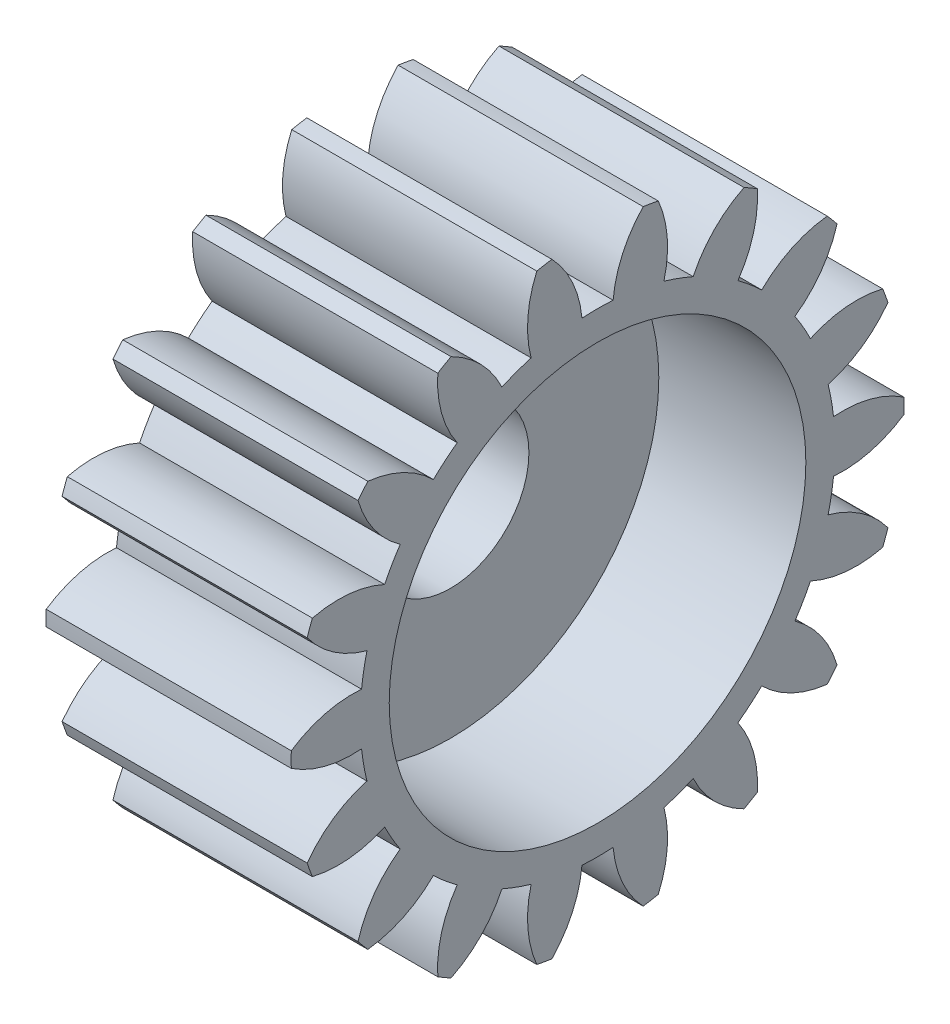
SolidWorks part; units mm, degrees
ref_plane "Plane1" through (0, 0, 0) normal (0, 0, 1) x (1, 0, 0)
ref_plane "Plane2" through (0, 0, 0) normal (0, 1, 0) x (1, 0, 0)
ref_plane "Plane3" through (0, 0, 0) normal (1, 0, 0) x (0, 0, -1)
sketch "HoldingSke" plane through (0, 0, 0) normal (0, 1, 0) x (1, 0, 0)
  line L0 (0, 0) -> (0.7608, -0.2472)
  line L1 (-15, 0) -> (100, 0) construction
  line L2 (0, 0) -> (-2.1039, 2.3779)
  line L3 (0, 0) -> (-11.863, 4.5341)
  line L4 (0, 0) -> (8.2133, 2.6687)
  line L5 (0, 0) -> (-46.8476, -17.4728)
  line L6 (0, 0) -> (-8.2896, -5.593)
  line L7 (-2.1039, 2.3779) -> (8.6586, 51.2059)
  line L8 (-76.2, 54.61) -> (-75.7, 54.61)
  line L9 (-71.009, 38.7566) -> (-53.1078, 45.2721)
  line L10 (-76.2, 71.12) -> (104.1128, 71.12)
  line L11 (0, 0) -> (-10, 0)
  line L12 (-76.2, 101.6) -> (-76.155, 101.6)
  line L13 (24.9733, 27.94) -> (52.9518, 28.4284)
  line L14 (24.9733, 27.94) -> (24.9743, 27.94)
  line L15 (24.9733, 27.94) -> (100.4006, 29.5858)
  line L16 (-63.627, -1.25) -> (-12.827, -1.25)
  circle A0 centre (0, 0) radius 1.5
  circle A1 centre (0, 0) radius 9.6865
  circle A2 centre (0, 0) radius 37.5
  circle A3 centre (0, 0) radius 1.5
  dimension "MHD" = 19.373
  dimension "Hub_dia" = 75
  dimension "Bore" = 3
  dimension "MBD" = 3
  dimension "Num_teeth" = 18
  dimension "Pitch" = 0.8
  dimension "Overall_len" = 50
  dimension "Show_teeth" = 18
  dimension "Thickness" = 10
  dimension "OAL" = 50.0001
  dimension "T_dim" = 0.5
  dimension "Ap" = 20
  dimension "H" = 19.05
  dimension "Pitch_radius" = 180.3128
  dimension "Width" = 10
  dimension "Backlash" = 0.045
  dimension "Addendum_fac" = 1
  dimension "Dedendum_fac" = 1.25
  dimension "Clearance_fac" = 0.25
  dimension "Dedendum_add" = 0.001
  dimension "Module" = 1.25
sketch "BasProSke" plane through (0, 0, 0) normal (0, 1, 0) x (1, 0, 0)
  line L0 (-10, 0) -> (60, 0) construction
  line L1 (0, 0) -> (0, 12.5)
  line L2 (0, 0) -> (10, 0)
  line L3 (10, 0) -> (10, 12.5)
  line L4 (10, 12.5) -> (0, 12.5)
  dimension "Thickness" = 10
  dimension "Diameter" = 25
revolve "Base-Revolve" add sketch "BasProSke" angle 360 about L0
sketch "TooCutSke" plane through (0, 0, 0) normal (1, 0, 0) x (0, 0, -1)
  line L1 (0, 0) -> (0, 107) construction
  line L2 (0, 0) -> (-1.0592, 11.2) construction
  line L3 (0, 0) -> (-3.8945, 22.0869) construction
  line L4 (-1.0592, 11.2) -> (-1.9473, 11.0434) construction
  arc A0 (0.6346, 9.6657) -> (-0.6346, 9.6657) centre (0, 0) ccw
  arc A1 (1.8837, 12.3829) -> (-1.8837, 12.3829) centre (0, 0) ccw
  circle A2 centre (0, 0) radius 11.25 construction
  circle A3 centre (0, 0) radius 10.5715 construction
  arc A4 (-0.6346, 9.6657) -> (-1.8837, 12.3829) centre (-5.1154, 9.2515) ccw
  arc A5 (1.8837, 12.3829) -> (0.6346, 9.6657) centre (5.1154, 9.2515) ccw
  dimension "Root_dia" = 19.373
  dimension "Overcut_dia" = 25.0508
  dimension "Pitch_dia" = 22.5
  dimension "Base_dia" = 21.1431
  dimension "Flank_rad" = 4.5
  dimension "Half_ang" = 10
  dimension "Half_CT" = 0.9018
extrude "ToothCut" cut sketch "TooCutSke" along normal through all
fillet "Breaks" [suppressed] radius 0.025
fillet "RootFillets" [suppressed] radius 0.3135
pattern_circular "TeethCuts" count 18 every 20 about axis through (-10, 0, 0) along (1, 0, 0) of "ToothCut", "RootFillets", "Breaks"
sketch "HubNeaOneSke" plane through (0, 0, 0) normal (-1, 0, 0) x (0, 0, 1)
  circle A0 centre (0, 0) radius 9.6865
  dimension "Diameter" = 19.373
extrude "HubNearOne" [suppressed] add sketch "HubNeaOneSke" along normal blind 40.0001
sketch "HubNeaBotSke" plane through (0, 0, 0) normal (-1, 0, 0) x (0, 0, 1)
  circle A0 centre (0, 0) radius 9.6865
  dimension "Diameter" = 19.373
extrude "HubNearBoth" [suppressed] add sketch "HubNeaBotSke" along normal blind 20
ref_plane "FarPln" through (10, 0, 0) normal (1, 0, 0) x (0, 0, -1)
sketch "HubFarSke" plane through (10, 0, 0) normal (1, 0, 0) x (0, 0, -1)
  circle A0 centre (0, 0) radius 9.6865
  dimension "Diameter" = 19.373
extrude "HubFar" [suppressed] add sketch "HubFarSke" along normal blind 20
sketch "BorSke" plane through (0, 0, 0) normal (1, 0, 0) x (0, 0, -1)
  circle A0 centre (0, 0) radius 1.5
  dimension "Diameter" = 3
extrude "Bore" cut sketch "BorSke" along normal mid plane 100.0001
sketch "KeySke" plane through (0, 0, 0) normal (1, 0, 0) x (0, 0, -1)
  line L0 (-0.6, 0) -> (-0.6, 2)
  line L1 (-0.6, 2) -> (0.6, 2)
  line L2 (0.6, 2) -> (0.6, 0)
  line L3 (0, 0) -> (0, 34) construction
  line L4 (-0.6, 0) -> (0.6, 0)
  dimension "Offset" = 2
  dimension "Width" = 1.2
extrude "Keyway" [suppressed] cut sketch "KeySke" along normal mid plane 100.0001
pattern_circular "Keyway2" [suppressed] count 2 every 90 about axis through (-10, 0, 0) along (1, 0, 0)
sketch "Sketch1" plane through (10, 0, 0) normal (1, 0, 0) x (0, 0, -1)
  circle A0 centre (0, 0) radius 8.5
  dimension "D1" = 17
extrude "Cut-Extrude1" cut sketch "Sketch1" against normal blind 6
sketch "Sketch2" plane through (4, 0, 0) normal (1, 0, 0) x (0, 0, -1)
  circle A0 centre (0, 0) radius 3.2
  dimension "D1" = 6.4
extrude "Cut-Extrude2" cut sketch "Sketch2" against normal through all
equation "' \"Module@HoldingSke\" = 6.35"
equation "' \"Num_teeth@HoldingSke\" = 12"
equation "' \"Ap@HoldingSke\" =  20"
equation "' \"Ap@HoldingSke\" = 20"
equation "' \"Width@HoldingSke\" = 0.5 * 25.4"
equation "' \"Hub_dia@HoldingSke\"= 1 * 25.4"
equation "' \"Hub_dia@HoldingSke\" = 1 * 25.4"
equation "' \"Overall_len@HoldingSke\" = 1.0 * 25.4"
equation "' \"Bore@HoldingSke\" = 0.75 * 25.4"
equation "' \"T_dim@HoldingSke\" = 0.1 * 25.4"
equation "' \"Width@KeySke\" = 0.25 * 25.4"
equation "' \"Show_teeth@HoldingSke\" = 13"
equation "' \"Backlash@HoldingSke\" = 0.009 * 25.4"
equation "' \"Addendum_fac@HoldingSke\" = 1.0"
equation "' \"Dedendum_fac@HoldingSke\" = 1.25"
equation "' \"Dedendum_add@HoldingSke\" = 0.00005 * 25.4"
equation "' \"Clearance_fac@HoldingSke\" = 0.25"
equation "\"Pitch@HoldingSke\" = 1 / \"Module@HoldingSke\""
equation "\"Overcut_dia@TooCutSke\" = (\"Num_teeth@HoldingSke\" + 2 * \"Addendum_fac@HoldingSke\") / \"Pitch@HoldingSke\" + 0.002 * 25.4"
equation "\"Pitch_dia@TooCutSke\" = \"Num_teeth@HoldingSke\" / \"Pitch@HoldingSke\""
equation "\"Base_dia@TooCutSke\" = \"Num_teeth@HoldingSke\" / \"Pitch@HoldingSke\" * cos((\"Ap@HoldingSke\"  * 3.14159265 / 180))"
equation "\"Root_dia@TooCutSke\" = (\"Num_teeth@HoldingSke\" + 2) / \"Pitch@HoldingSke\" - 2 * (\"Addendum_fac@HoldingSke\" + \"Dedendum_fac@HoldingSke\") / \"Pitch@HoldingSke\" - \"Dedendum_add@HoldingSke\" * 2"
equation "\"Half_ang@TooCutSke\" = 180 / \"Num_teeth@HoldingSke\""
equation "\"Half_CT@TooCutSke\" = \"Num_teeth@HoldingSke\" / \"Pitch@HoldingSke\" * sin((3.14159265 / 2 / \"Num_teeth@HoldingSke\")) / 2 - 7 * \"Backlash@HoldingSke\" / 4"
equation "\"Flank_rad@TooCutSke\" = \"Num_teeth@HoldingSke\" / \"Pitch@HoldingSke\" / 5"
equation "\"Radius@RootFillets\" = \"Clearance_fac@HoldingSke\" / \"Pitch@HoldingSke\" + \"Dedendum_add@HoldingSke\""
equation "\"Break_rad@Breaks\" = 0.02 / \"Pitch@HoldingSke\""
equation "\"Thickness@HoldingSke\" = \"Width@HoldingSke\""
equation "\"OAL@HoldingSke\" = \"Thickness@HoldingSke\""
equation "\"MHD@HoldingSke\" = (\"Num_teeth@HoldingSke\" + 2) / \"Pitch@HoldingSke\" - 2 * (\"Addendum_fac@HoldingSke\" + \"Dedendum_fac@HoldingSke\")  / \"Pitch@HoldingSke\" - \"Dedendum_add@HoldingSke\" * 2"
equation "\"MBD@HoldingSke\" = (\"Num_teeth@HoldingSke\" + 2) / \"Pitch@HoldingSke\" - 2 * (\"Addendum_fac@HoldingSke\" + \"Dedendum_fac@HoldingSke\")  / \"Pitch@HoldingSke\" - \"Dedendum_add@HoldingSke\" * 2 - 0.002 * 25.4"
equation "\"MHD@HoldingSke\" = ((sgn( \"MHD@HoldingSke\" - \"Hub_dia@HoldingSke\" )-1)*( \"MHD@HoldingSke\" - \"Hub_dia@HoldingSke\" ))/-2+ \"Hub_dia@HoldingSke\""
equation "\"MBD@HoldingSke\" = ((sgn( \"MBD@HoldingSke\" - \"Bore@HoldingSke\" )-1)*( \"MBD@HoldingSke\" - \"Bore@HoldingSke\" ))/-2+ \"Bore@HoldingSke\""
equation "\"OAL@HoldingSke\" = ((sgn( \"OAL@HoldingSke\" - \"Overall_len@HoldingSke\" )+1)*( \"OAL@HoldingSke\" - \"Overall_len@HoldingSke\" ))/2 + \"Overall_len@HoldingSke\" + 0.000002 * 25.4"
equation "\"Num_teeth@TeethCuts\" = int( \"Show_teeth@HoldingSke\" ) + 1"
equation "\"Num_teeth@TeethCuts\" = ((sgn( \"Num_teeth@TeethCuts\" - \"Num_teeth@HoldingSke\" )-1)*( \"Num_teeth@TeethCuts\" - \"Num_teeth@HoldingSke\" ))/-2+ \"Num_teeth@HoldingSke\""
equation "\"Num_teeth@TeethCuts\" = ((sgn( \"Num_teeth@TeethCuts\" - 2.0)+1)*( \"Num_teeth@TeethCuts\" - 2.0))/2 +2.0"
equation "\"Angle@TeethCuts\" = 360.0 / \"Num_teeth@HoldingSke\""
equation "\"Diameter@BasProSke\" = (\"Num_teeth@HoldingSke\" + 2 * \"Addendum_fac@HoldingSke\") / \"Pitch@HoldingSke\""
equation "\"Thickness@BasProSke\"  = \"Thickness@HoldingSke\""
equation "' \"Fillet_rad@BasProSke\" =  \"Thickness@HoldingSke\" * 0.05"
equation "' \"Fillet_rad@BasProSke\" = \"Thickness@HoldingSke\" * 0.05"
equation "\"MHD@HoldingSke\" = ((sgn( \"MHD@HoldingSke\" - \"Root_dia@TooCutSke\" )-1)*( \"MHD@HoldingSke\" - \"Root_dia@TooCutSke\" ))/-2+ \"Root_dia@TooCutSke\""
equation "\"Diameter@HubNeaOneSke\" = \"MHD@HoldingSke\""
equation "\"Length@HubNearOne\" = \"OAL@HoldingSke\" - \"Thickness@BasProSke\""
equation "\"Diameter@HubNeaBotSke\" = \"MHD@HoldingSke\""
equation "\"Length@HubNearBoth\" = ( \"OAL@HoldingSke\" - \"Thickness@BasProSke\" ) / 2.0"
equation "\"Thickness@FarPln\" = \"Thickness@BasProSke\""
equation "\"Diameter@HubFarSke\" = \"MHD@HoldingSke\""
equation "\"Length@HubFar\" = ( \"OAL@HoldingSke\" - \"Thickness@BasProSke\" ) / 2.0"
equation "\"Diameter@BorSke\" = \"MBD@HoldingSke\""
equation "\"D1@Bore\" = \"OAL@HoldingSke\" * 2.0"
equation "\"D1@Keyway\" = \"OAL@HoldingSke\" * 2.0"
equation "\"Offset@KeySke\" = \"T_dim@HoldingSke\" + \"MBD@HoldingSke\" / 2.0"
